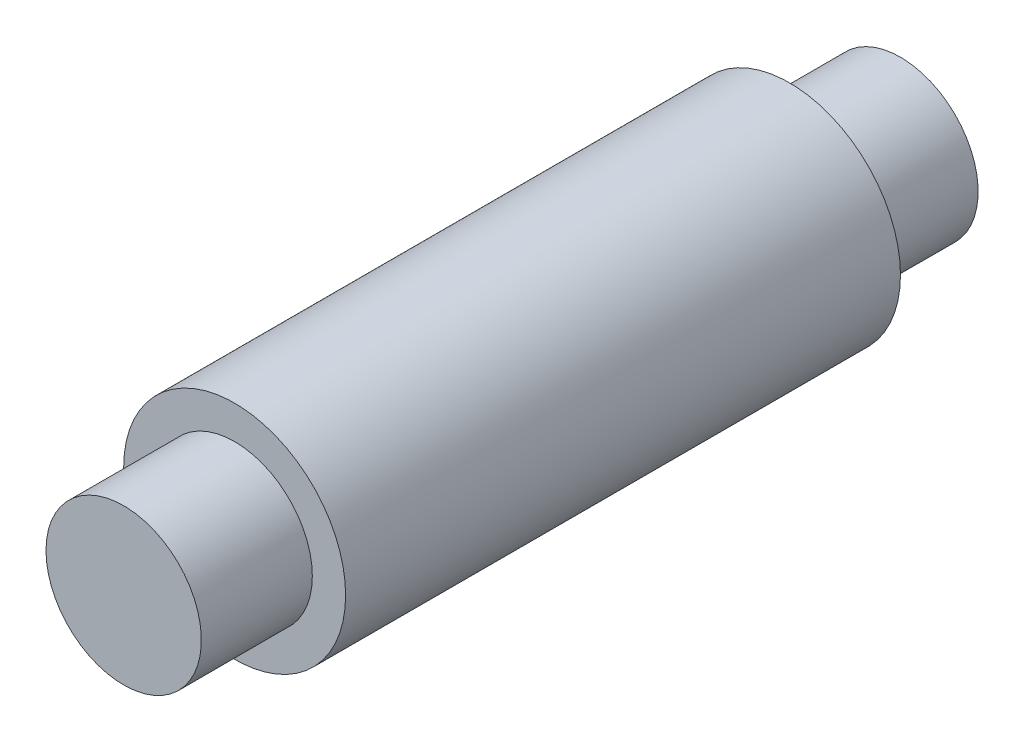
SolidWorks part; units mm, degrees
ref_plane "前视基准面" through (0, 0, 0) normal (0, 0, 1) x (1, 0, 0)
ref_plane "上视基准面" through (0, 0, 0) normal (0, 1, 0) x (1, 0, 0)
ref_plane "右视基准面" through (0, 0, 0) normal (1, 0, 0) x (0, 0, -1)
other "Configuration Table"
sketch "草图1" plane through (0, 0, 0) normal (0, 0, 1) x (1, 0, 0)
  circle A0 centre (0, 0) radius 2
  circle A1 centre (0, 0) radius 1.4
  dimension "D1" = 4
  dimension "D2" = 2.8
extrude "凸台-拉伸1" add sketch "草图1" along normal blind 10
sketch "草图2" plane through (0, 0, 0) normal (0, 0, -1) x (-1, 0, 0)
  circle A0 centre (0, 0) radius 1.4
  circle A1 centre (0, 0) radius 1.4 construction
extrude "凸台-拉伸2" add sketch "草图2" against normal up to surface (10 mm away) up to face at (2, 0, 10)
sketch "草图3" plane through (0, 0, 0) normal (0, 0, -1) x (-1, 0, 0)
  circle A0 centre (0, 0) radius 1.4
  dimension "D1" = 2.8
extrude "凸台-拉伸3" add sketch "草图3" along normal blind 2 and the other way blind 12 contours A0
